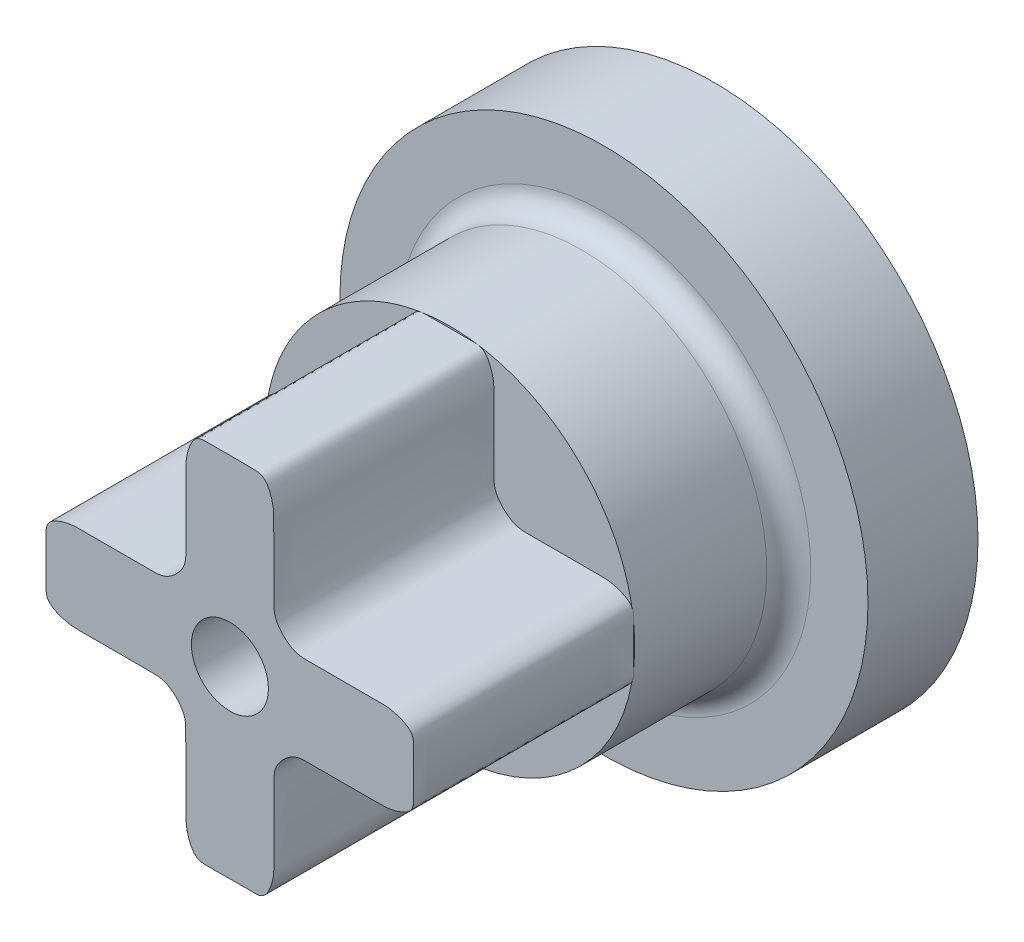
SolidWorks part; units mm, degrees
ref_plane "Front Plane" through (0, 0, 0) normal (0, 0, 1) x (1, 0, 0)
ref_plane "Top Plane" through (0, 0, 0) normal (0, 1, 0) x (1, 0, 0)
ref_plane "Right Plane" through (0, 0, 0) normal (1, 0, 0) x (0, 0, -1)
sketch "Sketch1" plane through (0, 0, 0) normal (0, 0, 1) x (1, 0, 0)
  circle A0 centre (0, 0) radius 8.4
  dimension "D1" = 16.8
extrude "Boss-Extrude1" add sketch "Sketch1" along normal blind 12
sketch "Sketch2" plane through (0, 0, 12) normal (0, 0, 1) x (1, 0, 0)
  line L0 (-2, -2) -> (-2, -8.358) construction
  line L1 (-8.3576, 2) -> (-2, 2) construction
  line L2 (-8.3576, 2) -> (-8.3576, -2) construction
  line L3 (-8.3576, -2) -> (-2, -2) construction
  line L4 (8.3473, 2) -> (8.3473, -2) construction
  line L5 (2, -2) -> (2, -8.358) construction
  line L7 (-2, 8.3167) -> (2, 8.3167) construction
  line L8 (-2, 8.3167) -> (-2, 2) construction
  line L9 (-2, -8.358) -> (2, -8.358) construction
  line L10 (2, 8.3167) -> (2, 2) construction
  line L13 (2, -2) -> (8.3473, -2) construction
  line L14 (2, 2) -> (8.3473, 2) construction
  spline S0 degree 3 poles (-1, 8.3167) (-0.3333, 8.3167) (0.3333, 8.3167) (1, 8.3167) (1.2077, 8.3167) (1.6231, 8.3167) (2, 7.3606) (2, 6.9452) (2, 6.7375) (2, 5.6847) (2, 4.632) (2, 3.5792) (2, 3.3304) (2, 2.8329) (2.8406, 2) (3.3381, 2) (3.5868, 2) (4.6447, 2) (5.7026, 2) (6.7605, 2) (6.9689, 2) (7.3857, 2) (8.3473, 1.6252) (8.3473, 1.2084) (8.3473, 1) (8.3473, 0.3333) (8.3473, -0.3333) (8.3473, -1) (8.3473, -1.2084) (8.3473, -1.6252) (7.3857, -2) (6.9689, -2) (6.7605, -2) (5.7026, -2) (4.6447, -2) (3.5868, -2) (3.3373, -2) (2.8382, -2) (2, -2.8408) (2, -3.3399) (2, -3.5895) (2, -4.6492) (2, -5.7088) (2, -6.7685) (2, -6.9771) (2, -7.3944) (1.626, -8.358) (1.2087, -8.358) (1, -8.358) (0.3333, -8.358) (-0.3333, -8.358) (-1, -8.358) (-1.2087, -8.358) (-1.626, -8.358) (-2, -7.3944) (-2, -6.9771) (-2, -6.7685) (-2, -5.7088) (-2, -4.6492) (-2, -3.5895) (-2, -3.3397) (-2, -2.8402) (-2.8401, -2) (-3.3397, -2) (-3.5894, -2) (-4.649, -2) (-5.7086, -2) (-6.7682, -2) (-6.9769, -2) (-7.3942, -2) (-8.3576, -1.6259) (-8.3576, -1.2086) (-8.3576, -1) (-8.3576, -0.3333) (-8.3576, 0.3333) (-8.3576, 1) (-8.3576, 1.2086) (-8.3576, 1.6259) (-7.3942, 2) (-6.9769, 2) (-6.7682, 2) (-5.7086, 2) (-4.649, 2) (-3.5894, 2) (-3.3405, 2) (-2.8426, 2) (-2, 2.8323) (-2, 3.3302) (-2, 3.5792) (-2, 4.632) (-2, 5.6847) (-2, 6.7375) (-2, 6.9452) (-2, 7.3606) (-1.6231, 8.3167) (-1.2077, 8.3167) (-1, 8.3167) (-0.3333, 8.3167) (0.3333, 8.3167) knots -0.010863 0 0 0 0.034871 0.034871 0.034871 0.045735 0.056598 0.067461 0.067461 0.067461 0.122529 0.122529 0.122529 0.13554 0.148552 0.161563 0.161563 0.161563 0.216898 0.216898 0.216898 0.227799 0.2387 0.249601 0.249601 0.249601 0.284472 0.284472 0.284472 0.295373 0.306274 0.317175 0.317175 0.317175 0.37251 0.37251 0.37251 0.385563 0.398617 0.41167 0.41167 0.41167 0.467098 0.467098 0.467098 0.478012 0.488926 0.49984 0.49984 0.49984 0.534712 0.534712 0.534712 0.545626 0.55654 0.567454 0.567454 0.567454 0.622882 0.622882 0.622882 0.635946 0.64901 0.662074 0.662074 0.662074 0.717499 0.717499 0.717499 0.728412 0.739326 0.75024 0.75024 0.75024 0.785111 0.785111 0.785111 0.796025 0.806938 0.817852 0.817852 0.817852 0.873277 0.873277 0.873277 0.886299 0.89932 0.912342 0.912342 0.912342 0.96741 0.96741 0.96741 0.978273 0.989137 1 1 1 1.034871 1.034871 1.034871 only from (-1, 8.3167) to (-1, 8.3167)
  dimension "D1" = 4
  dimension "D2" = 4
extrude "Boss-Extrude2" add sketch "Sketch2" along normal blind 10
sketch "Sketch3" plane through (0, 0, 0) normal (0, 0, -1) x (-1, 0, 0)
  circle A0 centre (0, 0) radius 12
  dimension "D1" = 24
extrude "Boss-Extrude3" add sketch "Sketch3" against normal blind 5
sketch "Sketch4" plane through (0, 0, 0) normal (0, 0, -1) x (-1, 0, 0)
  circle A0 centre (0, 0) radius 10.25
  dimension "D1" = 20.5
extrude "Cut-Extrude1" cut sketch "Sketch4" against normal blind 2.5
sketch "Sketch5" plane through (0, 0, 2.5) normal (0, 0, -1) x (-1, 0, 0)
  circle A0 centre (0, 0) radius 4.5
  dimension "D1" = 9
extrude "Cut-Extrude2" cut sketch "Sketch5" against normal blind 2.5
fillet "Fillet1" radius 1 1 edges at (-8.4, 0, 5)
sketch "Sketch6" plane through (0, 0, 5) normal (0, 0, -1) x (-1, 0, 0)
  circle A0 centre (0, 0) radius 3
  dimension "D1" = 6
extrude "Cut-Extrude3" cut sketch "Sketch6" against normal blind 3
sketch "Sketch7" plane through (0, 0, 8) normal (0, 0, -1) x (-1, 0, 0)
  circle A0 centre (0, 0) radius 1.75
  dimension "D1" = 3.5
extrude "Cut-Extrude4" cut sketch "Sketch7" against normal blind 14.5
